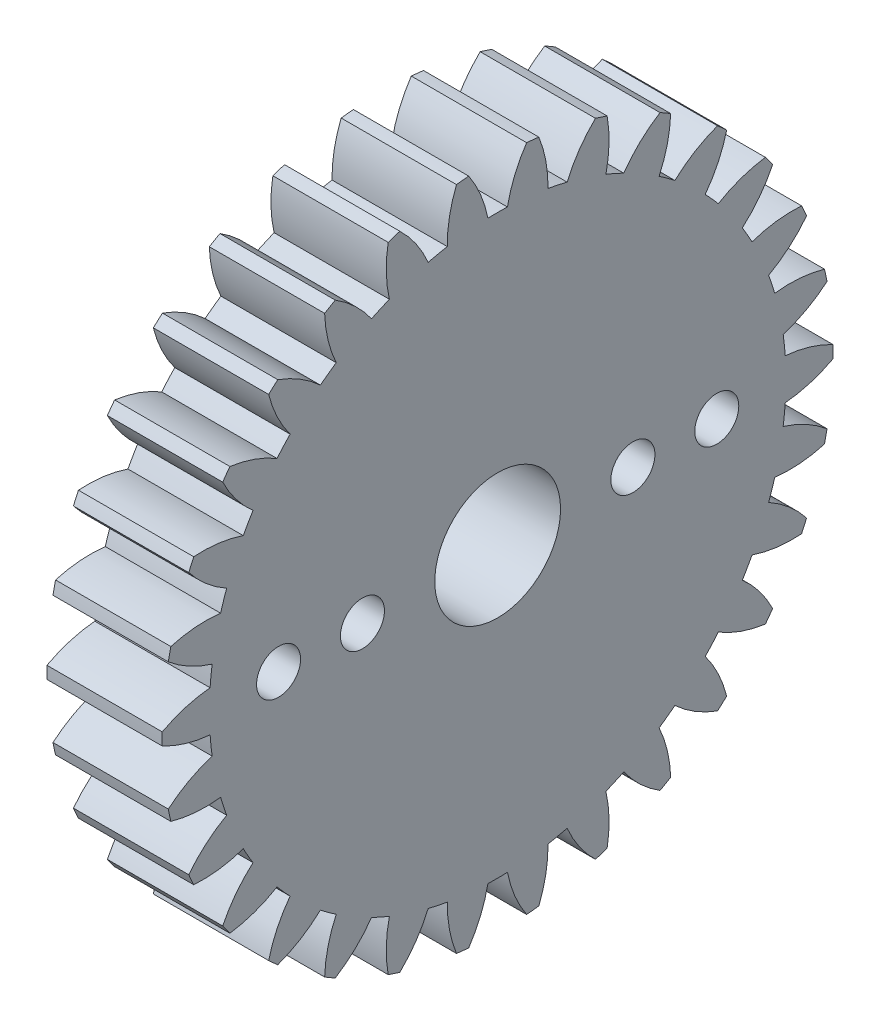
SolidWorks part; units mm, degrees
ref_plane "Plane1" through (0, 0, 0) normal (0, 0, 1) x (1, 0, 0)
ref_plane "Plane2" through (0, 0, 0) normal (0, 1, 0) x (1, 0, 0)
ref_plane "Plane3" through (0, 0, 0) normal (1, 0, 0) x (0, 0, -1)
sketch "HoldingSke" plane through (0, 0, 0) normal (0, 1, 0) x (1, 0, 0)
  line L0 (0, 0) -> (0.866, -0.5)
  line L1 (-15, 0) -> (100, 0) construction
  line L2 (0, 0) -> (-2.1039, 2.3779)
  line L3 (0, 0) -> (-11.863, 4.5341)
  line L4 (0, 0) -> (7.479, 4.318)
  line L5 (0, 0) -> (-46.8476, -17.4728)
  line L6 (0, 0) -> (-4.5593, -3.0762)
  line L7 (-2.1039, 2.3779) -> (8.6586, 51.2059)
  line L8 (-76.2, 54.61) -> (-76.1, 54.61)
  line L9 (-71.009, 38.7566) -> (-53.1078, 45.2721)
  line L10 (-76.2, 71.12) -> (104.1128, 71.12)
  line L11 (0, 0) -> (-5.5, 0)
  line L12 (-76.2, 101.6) -> (-76.162, 101.6)
  line L13 (24.9733, 27.94) -> (52.9518, 28.4284)
  line L14 (24.9733, 27.94) -> (24.9743, 27.94)
  line L15 (24.9733, 27.94) -> (100.4006, 29.5858)
  line L16 (-63.627, -1) -> (-12.827, -1)
  circle A0 centre (0, 0) radius 0.5
  circle A1 centre (0, 0) radius 13.749
  circle A2 centre (0, 0) radius 37.5
  circle A3 centre (0, 0) radius 0.5
  dimension "MHD" = 27.498
  dimension "Hub_dia" = 75
  dimension "Bore" = 1
  dimension "MBD" = 1
  dimension "Num_teeth" = 30
  dimension "Pitch" = 1
  dimension "Overall_len" = 50
  dimension "Show_teeth" = 30
  dimension "Thickness" = 5.5
  dimension "OAL" = 50.0001
  dimension "T_dim" = 0.1
  dimension "Ap" = 20
  dimension "H" = 19.05
  dimension "Pitch_radius" = 180.3128
  dimension "Width" = 5.5
  dimension "Backlash" = 0.038
  dimension "Addendum_fac" = 1
  dimension "Dedendum_fac" = 1.25
  dimension "Clearance_fac" = 0.25
  dimension "Dedendum_add" = 0.001
  dimension "Module" = 1
sketch "BasProSke" plane through (0, 0, 0) normal (0, 1, 0) x (1, 0, 0)
  line L0 (-10, 0) -> (60, 0) construction
  line L1 (0, 0) -> (0, 16)
  line L2 (0, 0) -> (5.5, 0)
  line L3 (5.5, 0) -> (5.5, 16)
  line L4 (5.5, 16) -> (0, 16)
  dimension "Thickness" = 5.5
  dimension "Diameter" = 32
revolve "Base-Revolve" add sketch "BasProSke" angle 360 about L0
sketch "TooCutSke" plane through (0, 0, 0) normal (1, 0, 0) x (0, 0, -1)
  line L1 (0, 0) -> (0, 107) construction
  line L2 (0, 0) -> (-0.8515, 14.9758) construction
  line L3 (0, 0) -> (-3.1323, 29.8014) construction
  line L4 (-0.8515, 14.9758) -> (-1.5661, 14.9007) construction
  arc A0 (0.4664, 13.7411) -> (-0.4664, 13.7411) centre (0, 0) ccw
  arc A1 (1.3975, 15.9644) -> (-1.3975, 15.9644) centre (0, 0) ccw
  circle A2 centre (0, 0) radius 15 construction
  circle A3 centre (0, 0) radius 14.0954 construction
  arc A4 (-0.4664, 13.7411) -> (-1.3975, 15.9644) centre (-6.3534, 12.5823) ccw
  arc A5 (1.3975, 15.9644) -> (0.4664, 13.7411) centre (6.3534, 12.5823) ccw
  dimension "Root_dia" = 27.498
  dimension "Overcut_dia" = 32.0508
  dimension "Pitch_dia" = 30
  dimension "Base_dia" = 28.1908
  dimension "Flank_rad" = 6
  dimension "Half_ang" = 6
  dimension "Half_CT" = 0.7185
extrude "ToothCut" cut sketch "TooCutSke" along normal through all
fillet "Breaks" [suppressed] radius 0.02
fillet "RootFillets" [suppressed] radius 0.251
pattern_circular "TeethCuts" count 30 every 12 about axis through (-10, 0, 0) along (1, 0, 0) of "ToothCut", "RootFillets", "Breaks"
sketch "HubNeaOneSke" plane through (0, 0, 0) normal (-1, 0, 0) x (0, 0, 1)
  circle A0 centre (0, 0) radius 13.749
  dimension "Diameter" = 27.498
extrude "HubNearOne" [suppressed] add sketch "HubNeaOneSke" along normal blind 44.5001
sketch "HubNeaBotSke" plane through (0, 0, 0) normal (-1, 0, 0) x (0, 0, 1)
  circle A0 centre (0, 0) radius 13.749
  dimension "Diameter" = 27.498
extrude "HubNearBoth" [suppressed] add sketch "HubNeaBotSke" along normal blind 22.25
ref_plane "FarPln" through (5.5, 0, 0) normal (1, 0, 0) x (0, 0, -1)
sketch "HubFarSke" plane through (5.5, 0, 0) normal (1, 0, 0) x (0, 0, -1)
  circle A0 centre (0, 0) radius 13.749
  dimension "Diameter" = 27.498
extrude "HubFar" [suppressed] add sketch "HubFarSke" along normal blind 22.25
sketch "BorSke" plane through (0, 0, 0) normal (1, 0, 0) x (0, 0, -1)
  circle A0 centre (0, 0) radius 0.5
  dimension "Diameter" = 1
extrude "Bore" cut sketch "BorSke" along normal mid plane 100.0001
sketch "KeySke" plane through (0, 0, 0) normal (1, 0, 0) x (0, 0, -1)
  line L0 (-0.05, 0) -> (-0.05, 0.6)
  line L1 (-0.05, 0.6) -> (0.05, 0.6)
  line L2 (0.05, 0.6) -> (0.05, 0)
  line L3 (0, 0) -> (0, 34) construction
  line L4 (-0.05, 0) -> (0.05, 0)
  dimension "Offset" = 0.6
  dimension "Width" = 0.1
extrude "Keyway" [suppressed] cut sketch "KeySke" along normal mid plane 100.0001
pattern_circular "Keyway2" [suppressed] count 2 every 90 about axis through (-10, 0, 0) along (1, 0, 0)
sketch "ｽｹｯﾁ1" plane through (5.5, 0, 0) normal (1, 0, 0) x (0, 0, -1)
  circle A0 centre (0, 0) radius 3
  circle A1 centre (6.45, 0) radius 1.05
  circle A2 centre (10.45, 0) radius 1.05
  circle A3 centre (-6.45, 0) radius 1.05
  circle A4 centre (-10.45, 0) radius 1.05
  dimension "D1" = 10.45
  dimension "D3" = 2.1
  dimension "D4" = 2.1
  dimension "D5" = 6
  dimension "D6" = 2.1
  dimension "D7" = 2.1
  dimension "D2" = 4
  dimension "D8" = 10.45
  dimension "D9" = 4
extrude "ｶｯﾄ - 押し出し1" cut sketch "ｽｹｯﾁ1" against normal through all
equation "' \"Module@HoldingSke\" = 6.35"
equation "' \"Num_teeth@HoldingSke\" = 12"
equation "' \"Ap@HoldingSke\" =  20"
equation "' \"Ap@HoldingSke\" = 20"
equation "' \"Width@HoldingSke\" = 0.5 * 25.4"
equation "' \"Hub_dia@HoldingSke\"= 1 * 25.4"
equation "' \"Hub_dia@HoldingSke\" = 1 * 25.4"
equation "' \"Overall_len@HoldingSke\" = 1.0 * 25.4"
equation "' \"Bore@HoldingSke\" = 0.75 * 25.4"
equation "' \"T_dim@HoldingSke\" = 0.1 * 25.4"
equation "' \"Width@KeySke\" = 0.25 * 25.4"
equation "' \"Show_teeth@HoldingSke\" = 13"
equation "' \"Backlash@HoldingSke\" = 0.009 * 25.4"
equation "' \"Addendum_fac@HoldingSke\" = 1.0"
equation "' \"Dedendum_fac@HoldingSke\" = 1.25"
equation "' \"Dedendum_add@HoldingSke\" = 0.00005 * 25.4"
equation "' \"Clearance_fac@HoldingSke\" = 0.25"
equation "\"Pitch@HoldingSke\" = 1 / \"Module@HoldingSke\""
equation "\"Overcut_dia@TooCutSke\" = (\"Num_teeth@HoldingSke\" + 2 * \"Addendum_fac@HoldingSke\") / \"Pitch@HoldingSke\" + 0.002 * 25.4"
equation "\"Pitch_dia@TooCutSke\" = \"Num_teeth@HoldingSke\" / \"Pitch@HoldingSke\""
equation "\"Base_dia@TooCutSke\" = \"Num_teeth@HoldingSke\" / \"Pitch@HoldingSke\" * cos((\"Ap@HoldingSke\"  * 3.14159265 / 180))"
equation "\"Root_dia@TooCutSke\" = (\"Num_teeth@HoldingSke\" + 2) / \"Pitch@HoldingSke\" - 2 * (\"Addendum_fac@HoldingSke\" + \"Dedendum_fac@HoldingSke\") / \"Pitch@HoldingSke\" - \"Dedendum_add@HoldingSke\" * 2"
equation "\"Half_ang@TooCutSke\" = 180 / \"Num_teeth@HoldingSke\""
equation "\"Half_CT@TooCutSke\" = \"Num_teeth@HoldingSke\" / \"Pitch@HoldingSke\" * sin((3.14159265 / 2 / \"Num_teeth@HoldingSke\")) / 2 - 7 * \"Backlash@HoldingSke\" / 4"
equation "\"Flank_rad@TooCutSke\" = \"Num_teeth@HoldingSke\" / \"Pitch@HoldingSke\" / 5"
equation "\"Radius@RootFillets\" = \"Clearance_fac@HoldingSke\" / \"Pitch@HoldingSke\" + \"Dedendum_add@HoldingSke\""
equation "\"Break_rad@Breaks\" = 0.02 / \"Pitch@HoldingSke\""
equation "\"Thickness@HoldingSke\" = \"Width@HoldingSke\""
equation "\"OAL@HoldingSke\" = \"Thickness@HoldingSke\""
equation "\"MHD@HoldingSke\" = (\"Num_teeth@HoldingSke\" + 2) / \"Pitch@HoldingSke\" - 2 * (\"Addendum_fac@HoldingSke\" + \"Dedendum_fac@HoldingSke\")  / \"Pitch@HoldingSke\" - \"Dedendum_add@HoldingSke\" * 2"
equation "\"MBD@HoldingSke\" = (\"Num_teeth@HoldingSke\" + 2) / \"Pitch@HoldingSke\" - 2 * (\"Addendum_fac@HoldingSke\" + \"Dedendum_fac@HoldingSke\")  / \"Pitch@HoldingSke\" - \"Dedendum_add@HoldingSke\" * 2 - 0.002 * 25.4"
equation "\"MHD@HoldingSke\" = ((sgn( \"MHD@HoldingSke\" - \"Hub_dia@HoldingSke\" )-1)*( \"MHD@HoldingSke\" - \"Hub_dia@HoldingSke\" ))/-2+ \"Hub_dia@HoldingSke\""
equation "\"MBD@HoldingSke\" = ((sgn( \"MBD@HoldingSke\" - \"Bore@HoldingSke\" )-1)*( \"MBD@HoldingSke\" - \"Bore@HoldingSke\" ))/-2+ \"Bore@HoldingSke\""
equation "\"OAL@HoldingSke\" = ((sgn( \"OAL@HoldingSke\" - \"Overall_len@HoldingSke\" )+1)*( \"OAL@HoldingSke\" - \"Overall_len@HoldingSke\" ))/2 + \"Overall_len@HoldingSke\" + 0.000002 * 25.4"
equation "\"Num_teeth@TeethCuts\" = int( \"Show_teeth@HoldingSke\" ) + 1"
equation "\"Num_teeth@TeethCuts\" = ((sgn( \"Num_teeth@TeethCuts\" - \"Num_teeth@HoldingSke\" )-1)*( \"Num_teeth@TeethCuts\" - \"Num_teeth@HoldingSke\" ))/-2+ \"Num_teeth@HoldingSke\""
equation "\"Num_teeth@TeethCuts\" = ((sgn( \"Num_teeth@TeethCuts\" - 2.0)+1)*( \"Num_teeth@TeethCuts\" - 2.0))/2 +2.0"
equation "\"Angle@TeethCuts\" = 360.0 / \"Num_teeth@HoldingSke\""
equation "\"Diameter@BasProSke\" = (\"Num_teeth@HoldingSke\" + 2 * \"Addendum_fac@HoldingSke\") / \"Pitch@HoldingSke\""
equation "\"Thickness@BasProSke\"  = \"Thickness@HoldingSke\""
equation "' \"Fillet_rad@BasProSke\" =  \"Thickness@HoldingSke\" * 0.05"
equation "' \"Fillet_rad@BasProSke\" = \"Thickness@HoldingSke\" * 0.05"
equation "\"MHD@HoldingSke\" = ((sgn( \"MHD@HoldingSke\" - \"Root_dia@TooCutSke\" )-1)*( \"MHD@HoldingSke\" - \"Root_dia@TooCutSke\" ))/-2+ \"Root_dia@TooCutSke\""
equation "\"Diameter@HubNeaOneSke\" = \"MHD@HoldingSke\""
equation "\"Length@HubNearOne\" = \"OAL@HoldingSke\" - \"Thickness@BasProSke\""
equation "\"Diameter@HubNeaBotSke\" = \"MHD@HoldingSke\""
equation "\"Length@HubNearBoth\" = ( \"OAL@HoldingSke\" - \"Thickness@BasProSke\" ) / 2.0"
equation "\"Thickness@FarPln\" = \"Thickness@BasProSke\""
equation "\"Diameter@HubFarSke\" = \"MHD@HoldingSke\""
equation "\"Length@HubFar\" = ( \"OAL@HoldingSke\" - \"Thickness@BasProSke\" ) / 2.0"
equation "\"Diameter@BorSke\" = \"MBD@HoldingSke\""
equation "\"D1@Bore\" = \"OAL@HoldingSke\" * 2.0"
equation "\"D1@Keyway\" = \"OAL@HoldingSke\" * 2.0"
equation "\"Offset@KeySke\" = \"T_dim@HoldingSke\" + \"MBD@HoldingSke\" / 2.0"
